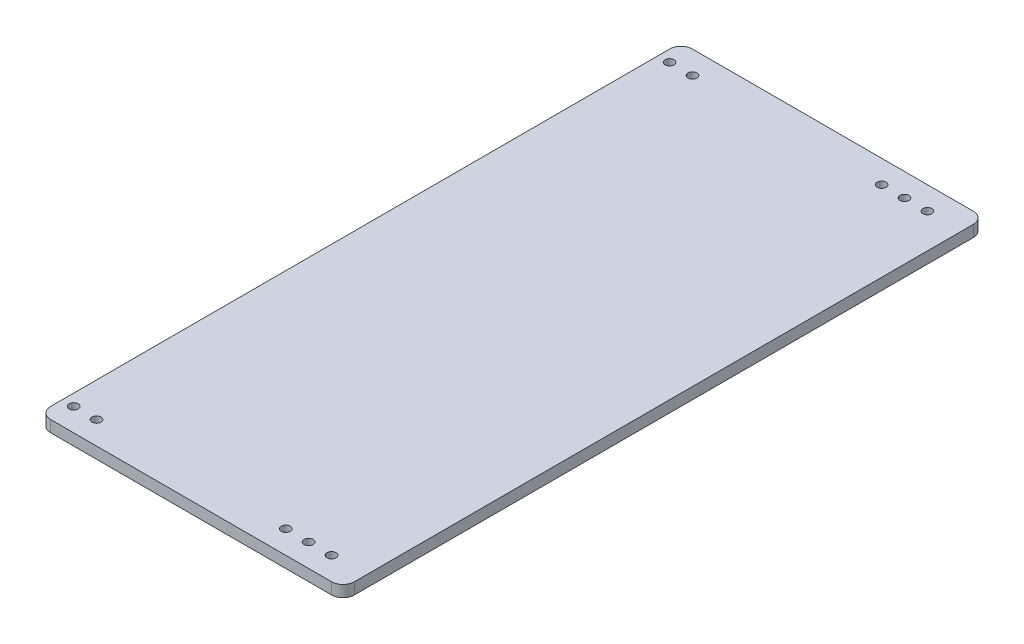
SolidWorks part; units mm, degrees
material "PC High Viscosity"
ref_plane "Front Plane" through (0, 0, 0) normal (0, 0, 1) x (1, 0, 0)
ref_plane "Top Plane" through (0, 0, 0) normal (0, 1, 0) x (1, 0, 0)
ref_plane "Right Plane" through (0, 0, 0) normal (1, 0, 0) x (0, 0, -1)
sketch "Sketch1" plane through (0, 0, 0) normal (0, 1, 0) x (1, 0, 0)
  line L1 (-84.1375, -177.8) -> (84.1375, -177.8)
  line L2 (-84.1375, -177.8) -> (-84.1375, 177.8)
  line L3 (-84.1375, 177.8) -> (84.1375, 177.8)
  line L4 (84.1375, -177.8) -> (84.1375, 177.8)
  line L5 (-84.1375, -177.8) -> (84.1375, 177.8) construction
  line L6 (-84.1375, 177.8) -> (84.1375, -177.8) construction
  point P0 (0, 0)
  dimension "D1" = 168.275
  dimension "D2" = 355.6
extrude "Boss-Extrude1" add sketch "Sketch1" along normal blind 6.35
sketch "Sketch2" plane through (0, 6.35, 0) normal (0, 1, 0) x (1, 0, 0)
  line L0 (84.1375, -177.8) -> (84.1375, 177.8) construction
  line L1 (-84.1375, -177.8) -> (84.1375, -177.8) construction
  line L2 (-84.1375, 0) -> (84.1375, 0) construction
  line L3 (-84.1375, 177.8) -> (-84.1375, -177.8) construction
  line L4 (0, 177.8) -> (0, -177.8) construction
  line L5 (84.1375, 177.8) -> (-84.1375, 177.8) construction
  circle A0 centre (77.7875, -165.1) radius 2.4892 construction
  circle A1 centre (65.0875, -165.1) radius 2.4892
  circle A2 centre (52.3875, -165.1) radius 2.4892
  circle A3 centre (39.6875, -165.1) radius 2.4892
  circle A4 centre (77.7875, 165.1) radius 2.4892 construction
  circle A5 centre (65.0875, 165.1) radius 2.4892
  circle A6 centre (52.3875, 165.1) radius 2.4892
  circle A7 centre (39.6875, 165.1) radius 2.4892
  circle A8 centre (77.7875, 165.1) radius 2.4892 construction
  circle A9 centre (65.0875, 165.1) radius 2.4892
  circle A10 centre (52.3875, 165.1) radius 2.4892
  circle A11 centre (39.6875, 165.1) radius 2.4892
  circle A12 centre (-77.7875, -165.1) radius 2.4892
  circle A13 centre (-65.0875, -165.1) radius 2.4892
  circle A14 centre (-52.3875, -165.1) radius 2.4892 construction
  circle A15 centre (-39.6875, -165.1) radius 2.4892 construction
  circle A16 centre (-77.7875, 165.1) radius 2.4892
  circle A17 centre (-65.0875, 165.1) radius 2.4892
  circle A18 centre (-52.3875, 165.1) radius 2.4892 construction
  circle A19 centre (-39.6875, 165.1) radius 2.4892 construction
  dimension "D1" = 4.9784
  dimension "D2" = 6.35
  dimension "D3" = 12.7
  dimension "D5" = 12.7
  dimension "D4" = 4
extrude "Cut-Extrude2" cut sketch "Sketch2" against normal through all contours A15 | A14 | A13 | A12 | A4 | A5 | A6 | A7 | A16 | A17 | A18 | A19 | A3 | A2 | A1 | A0
fillet "Fillet1" radius 6.35 4 edges at (84.1375, 3.175, 177.8) (-84.1375, 3.175, 177.8) (-84.1375, 3.175, -177.8) (84.1375, 3.175, -177.8)
